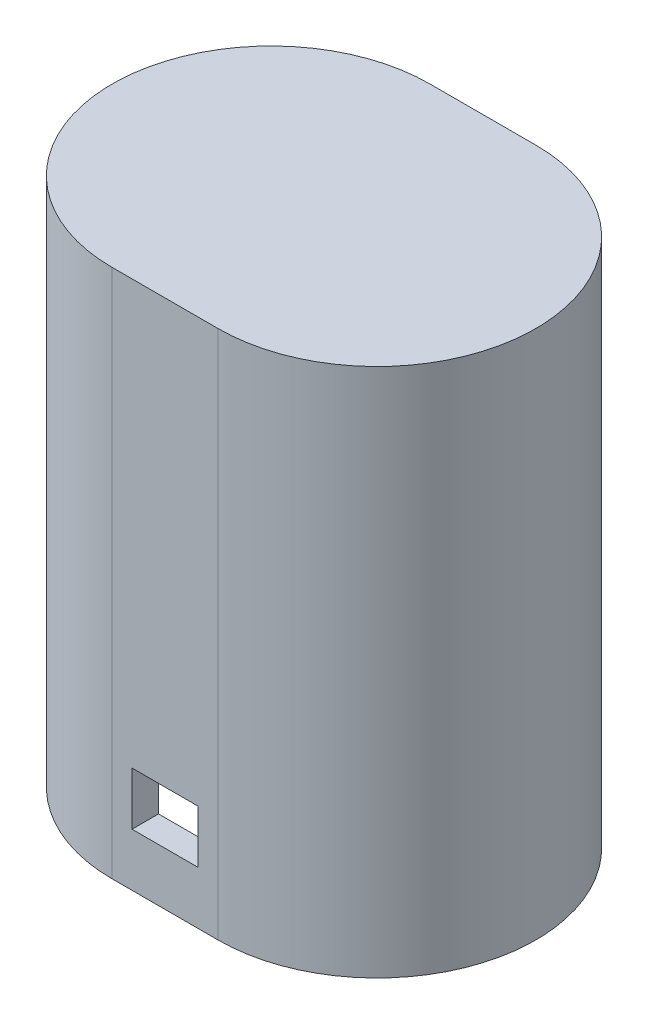
SolidWorks part; units mm, degrees
ref_plane "Front Plane" through (0, 0, 0) normal (0, 0, 1) x (1, 0, 0)
ref_plane "Top Plane" through (0, 0, 0) normal (0, 1, 0) x (1, 0, 0)
ref_plane "Right Plane" through (0, 0, 0) normal (1, 0, 0) x (0, 0, -1)
sketch "Sketch1" plane through (0, 0, 0) normal (0, 1, 0) x (1, 0, 0)
  line L0 (-2, -6) -> (2, -6)
  line L1 (-2, 6) -> (2, 6)
  line L2 (-3.5809, 0) -> (7.3013, 0) construction
  arc A1 (-2, 6) -> (-2, -6) centre (-2, 0) ccw
  arc A2 (2, -6) -> (2, 6) centre (2, 0) ccw
  point P5 (0, 6)
  point P9 (0, -6)
  point P12 (0, 0)
  point P13 (0, 0)
  point P14 (-8, 0)
  point P15 (8, 0)
  dimension "D1" = 12
  dimension "D2" = 16
extrude "Boss-Extrude1" add sketch "Sketch1" along normal blind 20
shell "Shell1" thickness 1
sketch "Sketch2" plane through (0, 0, 6) normal (0, 0, 1) x (1, 0, 0)
  line L0 (-2, 0) -> (2, 0) construction
  line L1 (-1.25, 4) -> (1.25, 4)
  line L2 (-1.25, 4) -> (-1.25, 2)
  line L3 (-1.25, 2) -> (1.25, 2)
  line L4 (1.25, 4) -> (1.25, 2)
  point P4 (0, 2)
  dimension "D1" = 2
  dimension "D2" = 2.5
  dimension "D3" = 2
extrude "Cut-Extrude1" cut sketch "Sketch2" against normal through all both and the other way through all
